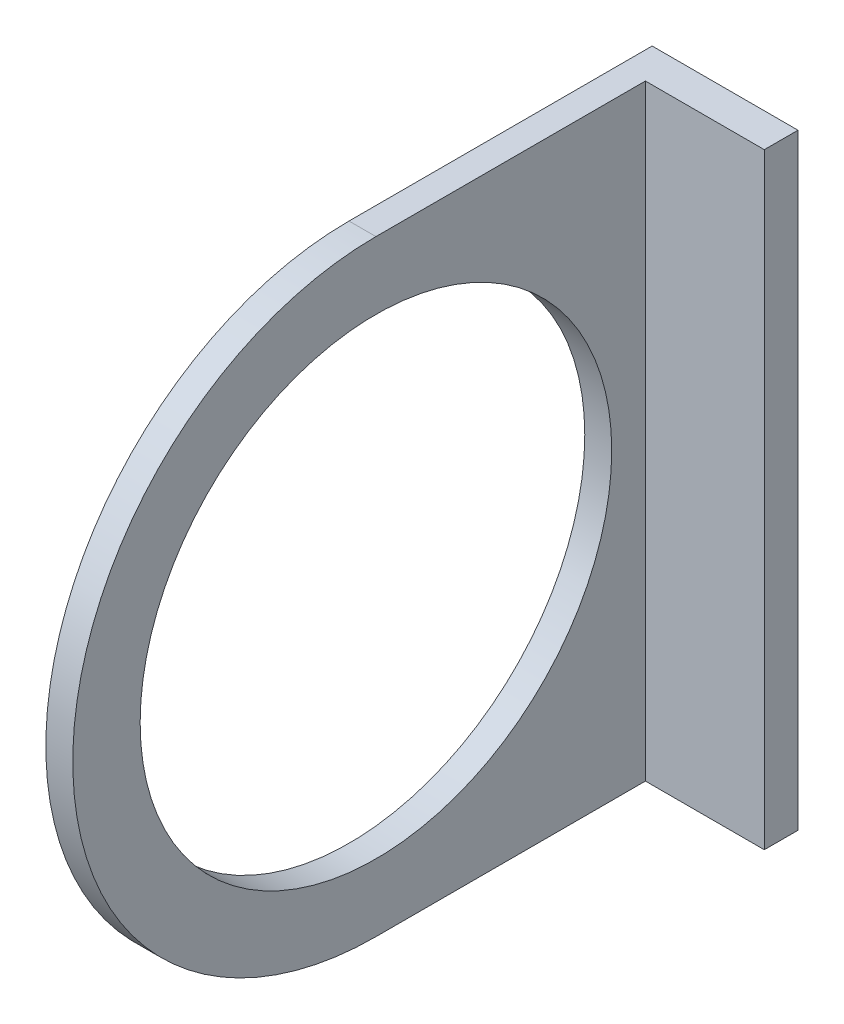
SolidWorks part; units mm, degrees
ref_plane "前视基准面" through (0, 0, 0) normal (0, 0, 1) x (1, 0, 0)
ref_plane "上视基准面" through (0, 0, 0) normal (0, 1, 0) x (1, 0, 0)
ref_plane "右视基准面" through (0, 0, 0) normal (1, 0, 0) x (0, 0, -1)
other "Configuration Table"
sketch "草图1" plane through (0, 0, 0) normal (0, 1, 0) x (1, 0, 0)
  line L0 (0, 0) -> (43.3, 0)
  line L1 (43.3, 0) -> (43.3, -10)
  line L2 (43.3, -10) -> (8, -10)
  line L3 (8, -10) -> (8, -300)
  line L4 (8, -300) -> (0, -300)
  line L5 (0, -300) -> (0, 0)
  dimension "D1" = 35.3
  dimension "D2" = 290
  dimension "D3" = 10
  dimension "D4" = 8
extrude "凸台-拉伸1" add sketch "草图1" along normal blind 180
sketch "草图2" plane through (8, 0, 0) normal (1, 0, 0) x (0, 0, -1)
  line L0 (-318.0541, 90) -> (-40.874, 90) construction
  line L1 (-300, 180) -> (-10, 180) construction
  line L2 (-300, 0) -> (-10, 0) construction
  line L3 (-90, 0) -> (-300, 0)
  line L4 (-300, 0) -> (-300, 180)
  line L5 (-300, 180) -> (-90, 180)
  line L6 (-10, 180) -> (-10, 0) construction
  arc A0 (-90, 180) -> (-90, 0) centre (-90, 90) ccw
  circle A1 centre (-90, 90) radius 70
  dimension "D2" = 140
  dimension "D1" = 80
extrude "切除-拉伸1" cut sketch "草图2" against normal blind 180
